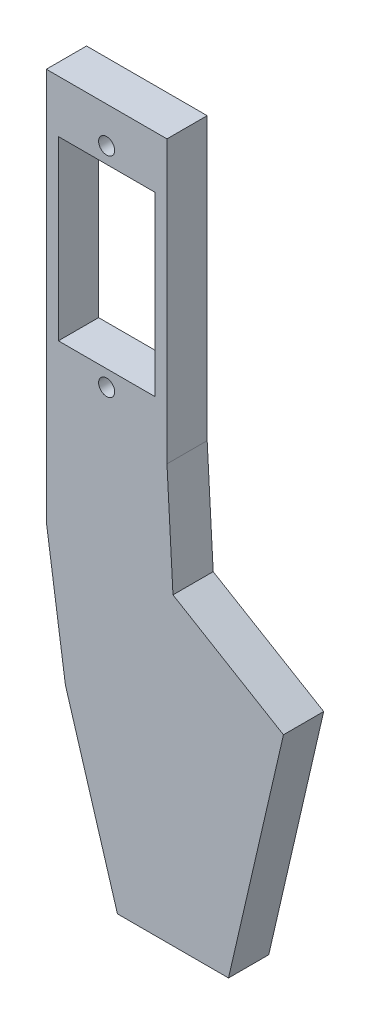
SolidWorks part; units mm, degrees
ref_plane "Front Plane" through (0, 0, 0) normal (0, 0, 1) x (1, 0, 0)
ref_plane "Top Plane" through (0, 0, 0) normal (0, 1, 0) x (1, 0, 0)
ref_plane "Right Plane" through (0, 0, 0) normal (1, 0, 0) x (0, 0, -1)
sketch "Sketch1" plane through (0, 0, 0) normal (0, 0, 1) x (1, 0, 0)
  line L1 (-22.6541, 17.9281) -> (-7.6541, 17.9281)
  line L2 (-22.6541, 17.9281) -> (-22.6541, -17.0719)
  line L3 (-22.6541, -17.0719) -> (-7.6541, -17.0719)
  line L4 (-7.6541, 17.9281) -> (-7.6541, -17.0719)
  line L5 (-22.6541, 17.9281) -> (-7.6541, -17.0719) construction
  line L6 (-22.6541, -17.0719) -> (-7.6541, 17.9281) construction
  point P0 (-15.1541, 0.4281)
  dimension "D1" = 15
  dimension "D2" = 35
extrude "Boss-Extrude1" add sketch "Sketch1" along normal blind 5
sketch "Sketch2" plane through (0, 0, 5) normal (0, 0, 1) x (1, 0, 0)
  line L4 (-9.1541, 11.4281) -> (-21.1541, 11.4281)
  line L5 (-21.1541, 11.4281) -> (-21.1541, -10.5719)
  line L6 (-21.1541, -10.5719) -> (-9.1541, -10.5719)
  line L7 (-9.1541, -10.5719) -> (-9.1541, 11.4281)
  circle A0 centre (-15.1541, -12.5719) radius 1
  circle A1 centre (-15.1541, 13.4281) radius 1
  dimension "D3" = 12
  dimension "D4" = 22
extrude "Cut-Extrude1" cut sketch "Sketch2" against normal blind 5
sketch "Sketch3" plane through (0, 0, 5) normal (0, 0, 1) x (1, 0, 0)
  line L0 (-22.6541, -17.0719) -> (-22.6541, -30.8042)
  line L1 (-22.6541, -30.8042) -> (-20.2826, -47.191)
  line L2 (-20.2826, -47.191) -> (-17.3594, -56.865)
  line L3 (-17.3594, -56.865) -> (-13.8112, -68.6075)
  line L4 (-13.8112, -68.6075) -> (0, -68.6075)
  line L5 (0, -68.6075) -> (6.8324, -38.9976)
  line L6 (6.8324, -38.9976) -> (-6.9056, -30.8042)
  line L7 (-6.9056, -30.8042) -> (-7.6541, -17.0719)
  line L8 (-7.6541, -17.0719) -> (-22.6541, -17.0719)
extrude "Boss-Extrude2" add sketch "Sketch3" against normal blind 5
